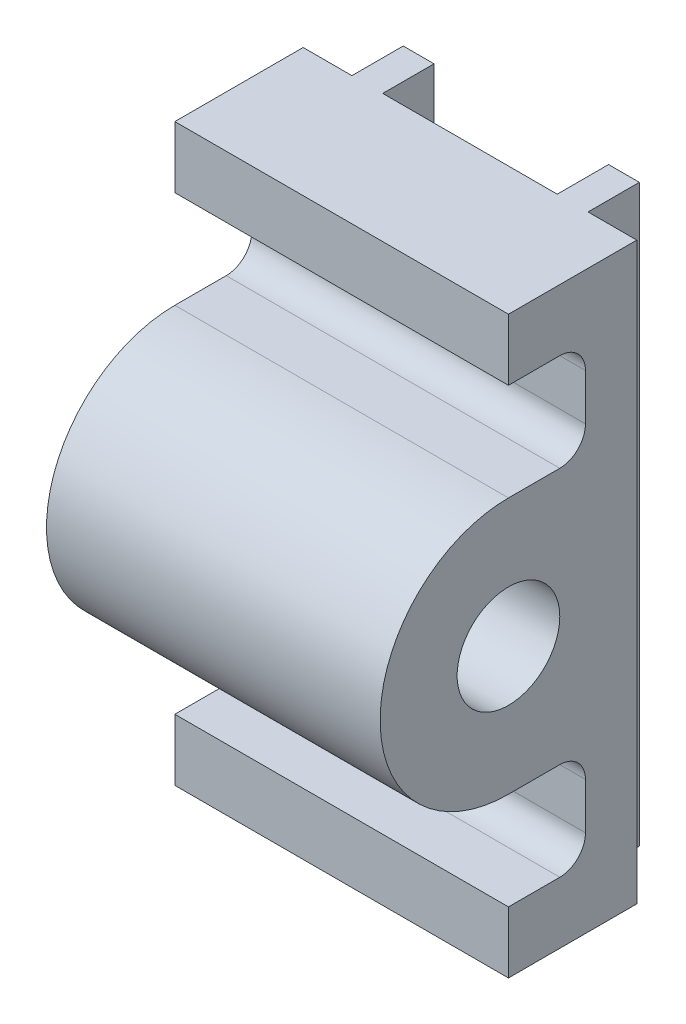
SolidWorks part; units mm, degrees
ref_plane "Front Plane" through (0, 0, 0) normal (1, 0, 0) x (0, 1, 0)
ref_plane "Top Plane" through (0, 0, 0) normal (0, 0, 1) x (0, 1, 0)
ref_plane "Right Plane" through (0, 0, 0) normal (0, 1, 0) x (-1, 0, 0)
sketch "Sketch1" plane through (0, 0, 0) normal (1, 0, 0) x (0, 1, 0)
  line L0 (0, 0) -> (30987.2242, 0) construction
  line L1 (0, 0) -> (0, 30987.2242) construction
  line L2 (-25, 0) -> (-25, -10)
  line L3 (-30, -15) -> (-39, -15)
  line L4 (-44, -10) -> (-44, 0)
  line L5 (-44, 0) -> (-56, 0)
  line L6 (-56, 0) -> (-56, -25)
  line L7 (-56, -25) -> (56, -25)
  line L8 (56, 0) -> (56, -25)
  line L9 (44, 0) -> (56, 0)
  line L10 (44, -10) -> (44, 0)
  line L11 (30, -15) -> (39, -15)
  line L12 (25, 0) -> (25, -10)
  circle A0 centre (0, 0) radius 10
  arc A1 (25, 0) -> (-25, 0) centre (0, 0) ccw
  arc A2 (-25, -10) -> (-30, -15) centre (-30, -10) cw
  arc A3 (-39, -15) -> (-44, -10) centre (-39, -10) cw
  arc A4 (39, -15) -> (44, -10) centre (39, -10) ccw
  arc A5 (25, -10) -> (30, -15) centre (30, -10) ccw
  point P29 (0, -25)
  dimension "D1" = 20
  dimension "D2" = 50
  dimension "D3" = 5
  dimension "D4" = 9
  dimension "D5" = 25
  dimension "D6" = 15
  dimension "D7" = 56
extrude "Boss-Extrude1" add sketch "Sketch1" along normal mid plane 65
sketch "Sketch2" plane through (0, 0, -25) normal (0, 0, -1) x (1, 0, 0)
  line L0 (0, 0) -> (0, 57.9624) construction
  line L1 (32.5, 56) -> (-32.5, 56) construction
  line L2 (-23, 56) -> (-17, 56)
  line L3 (-23, 56) -> (-23, -56)
  line L4 (-23, -56) -> (-17, -56)
  line L5 (-17, 56) -> (-17, -56)
  line L6 (32.5, -56) -> (-32.5, -56) construction
  line L7 (23, -56) -> (17, -56)
  line L8 (23, 56) -> (23, -56)
  line L9 (23, 56) -> (17, 56)
  line L10 (17, 56) -> (17, -56)
  dimension "D1" = 6
  dimension "D2" = 34
extrude "Boss-Extrude2" add sketch "Sketch2" along normal blind 10
